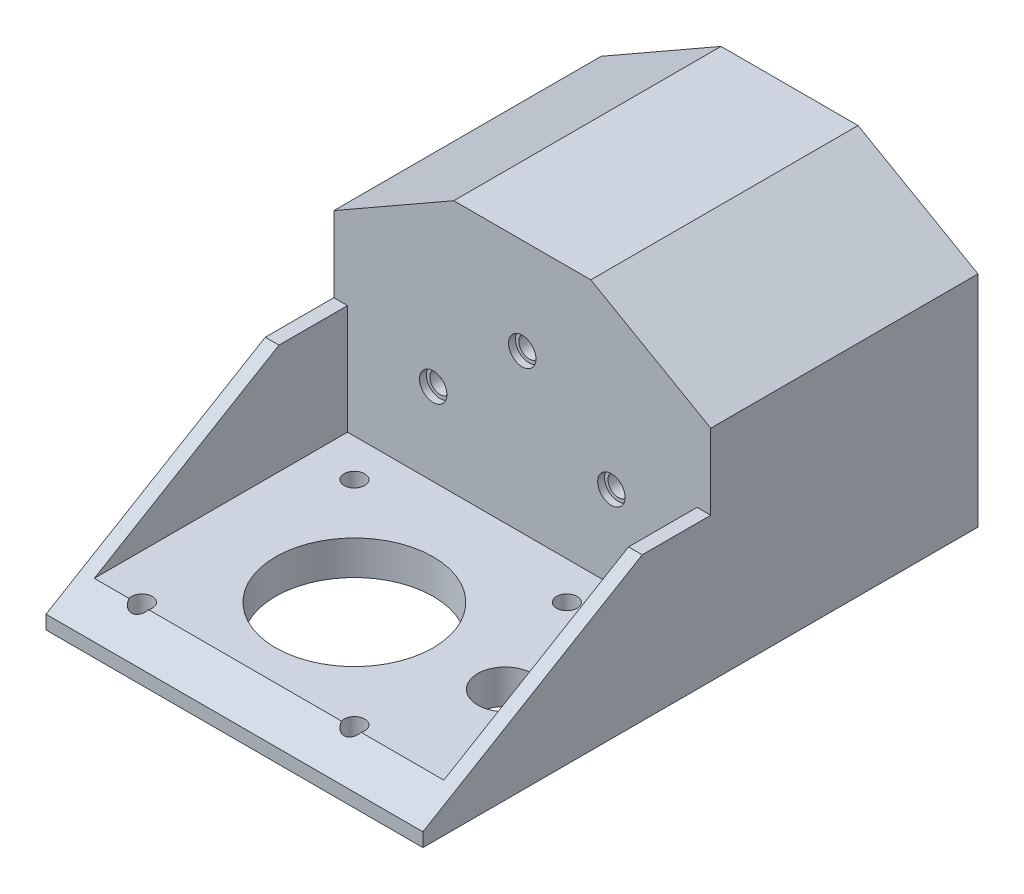
SolidWorks part; units mm, degrees
material "ABS"
ref_plane "Front Plane" through (0, 0, 0) normal (0, 0, 1) x (1, 0, 0)
ref_plane "Top Plane" through (0, 0, 0) normal (0, 1, 0) x (1, 0, 0)
ref_plane "Right Plane" through (0, 0, 0) normal (1, 0, 0) x (0, 0, -1)
sketch "Sketch1" plane through (0, 0, 0) normal (0, 0, 1) x (1, 0, 0)
  line L0 (0, 0) -> (55, 0)
  line L1 (55, 0) -> (55, 32)
  line L2 (55, 32) -> (37.5, 42)
  line L3 (37.5, 42) -> (17.5, 42)
  line L4 (17.5, 42) -> (0, 32)
  line L5 (0, 32) -> (0, 0)
  dimension "D1" = 55
  dimension "D2" = 42
  dimension "D3" = 32
  dimension "D4" = 20
extrude "Boss-Extrude1" add sketch "Sketch1" along normal blind 39
sketch "Sketch2" plane through (0, 0, 39) normal (0, 0, 1) x (1, 0, 0)
  line L0 (55, 0) -> (55, 32) construction
  line L1 (55, 5) -> (0, 5)
  line L2 (55, 5) -> (55, 0)
  line L3 (55, 0) -> (0, 0)
  line L4 (0, 5) -> (0, 0)
  dimension "D1" = 5
extrude "Boss-Extrude2" add sketch "Sketch2" along normal blind 42
sketch "Sketch3" plane through (0, 5, 0) normal (0, 1, 0) x (1, 0, 0)
  line L0 (55, -39) -> (0, -39) construction
  line L2 (55, -81) -> (55, -39) construction
  line L5 (24, -60) -> (24, 13.4963) construction
  line L6 (24, -60) -> (67.4103, -60) construction
  circle A0 centre (24, -60) radius 11.5
  circle A1 centre (8.5, -44.5) radius 1.5
  circle A2 centre (39.5, -44.5) radius 1.5
  circle A3 centre (39.5, -75.5) radius 1.5
  circle A4 centre (8.5, -75.5) radius 1.5
  circle A5 centre (46, -60) radius 4
  dimension "D1" = 23
  dimension "D2" = 21
  dimension "D3" = 9
  dimension "D4" = 31
  dimension "D5" = 31
  dimension "D6" = 15.5
  dimension "D7" = 15.5
  dimension "D8" = 3
  dimension "D9" = 22
  dimension "D10" = 8
extrude "Cut-Extrude1" cut sketch "Sketch3" against normal through all
sketch "Sketch4" plane through (0, 0, 39) normal (0, 0, 1) x (1, 0, 0)
  line L0 (27.5, 43.7016) -> (27.5, -3.1108) construction
  line L1 (55, 5) -> (55, 32) construction
  line L2 (55, 5) -> (0, 5) construction
  line L3 (37.5, 42) -> (17.5, 42) construction
  line L4 (27.5, 44.4782) -> (27.5, -5.1262) construction
  circle A0 centre (27.5, 28) radius 1.5
  circle A1 centre (40.5, 17) radius 1.5
  circle A3 centre (14.5, 17) radius 1.5
  dimension "D2" = 3
  dimension "D3" = 12
  dimension "D5" = 14
  dimension "D1" = 27.5
  dimension "D4" = 13
extrude "Cut-Extrude2" cut sketch "Sketch4" against normal through all
sketch "Sketch5" plane through (0, 0, 39) normal (0, 0, 1) x (1, 0, 0)
  circle A0 centre (27.5, 28) radius 2
  circle A1 centre (40.5, 17) radius 2
  circle A2 centre (14.5, 17) radius 2
  dimension "D1" = 4
extrude "Cut-Extrude3" cut sketch "Sketch5" against normal blind 1
sketch "Sketch6" plane through (0, 5, 0) normal (0, 1, 0) x (1, 0, 0)
  line L0 (55, -81) -> (0, -81) construction
  line L1 (0, -39) -> (2, -39)
  line L2 (0, -39) -> (0, -81)
  line L3 (0, -81) -> (2, -81)
  line L4 (2, -39) -> (2, -81)
  line L5 (55, -39) -> (0, -39) construction
  line L6 (55, -39) -> (53, -39)
  line L7 (55, -39) -> (55, -81)
  line L8 (55, -81) -> (53, -81)
  line L9 (53, -39) -> (53, -81)
  line L10 (55, -81) -> (55, -39) construction
  dimension "D1" = 2
  dimension "D2" = 2
extrude "Boss-Extrude3" add sketch "Sketch6" along normal blind 16
sketch "Sketch7" plane through (55, 0, 0) normal (1, 0, 0) x (0, 0, -1)
  line L0 (-49, 21) -> (-81, 21)
  line L1 (-81, 0) -> (-81, 21) construction
  line L2 (-81, 2) -> (-49, 21)
  line L3 (-81, 21) -> (-39, 21) construction
  line L4 (-81, 21) -> (-81, 2)
  line L5 (-81, 0) -> (0, 0) construction
  dimension "D1" = 2
  dimension "D2" = 32
extrude "Cut-Extrude4" cut sketch "Sketch7" against normal blind 100
equation "\"A\"=55"
equation "\"D1@Sketch1\"=\"A\""
equation "\"D1@Sketch4\"=\"A\"/2"
